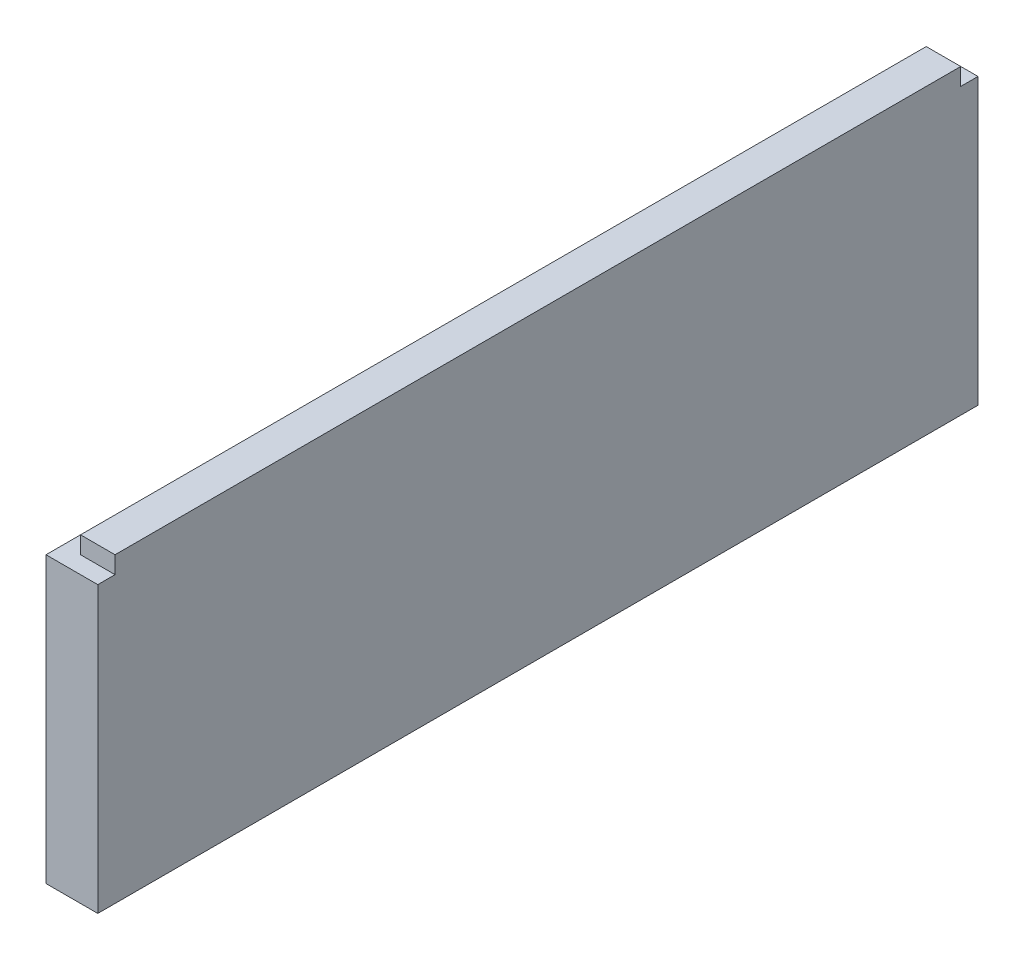
SolidWorks part; units mm, degrees
material "Сосна"
ref_plane "Спереди" through (0, 0, 0) normal (0, 0, 1) x (1, 0, 0)
ref_plane "Сверху" through (0, 0, 0) normal (0, 1, 0) x (1, 0, 0)
ref_plane "Справа" through (0, 0, 0) normal (1, 0, 0) x (0, 0, -1)
sketch "Эскиз1" plane through (0, 0, 0) normal (0, 0, 1) x (1, 0, 0)
  line L0 (0, 0) -> (10, 0)
  line L2 (10, 0) -> (30, 0)
  line L3 (30, 0) -> (30, 175)
  line L5 (10, 175) -> (10, 165)
  line L6 (10, 165) -> (0, 165)
  line L7 (0, 165) -> (0, 0)
  line L8 (30, 175) -> (10, 175)
  dimension "D1" = 175
  dimension "D2" = 30
  dimension "D3" = 10
  dimension "D5" = 10
extrude "Бобышка-Вытянуть1" add sketch "Эскиз1" along normal blind 510
sketch "Эскиз2" plane through (30, 0, 0) normal (1, 0, 0) x (0, 0, -1)
  line L0 (-10, 175) -> (0, 175)
  line L1 (-510, 175) -> (-500, 175)
  line L2 (-510, 175) -> (-510, 165)
  line L3 (-510, 165) -> (-500, 165)
  line L4 (-500, 175) -> (-500, 165)
  line L5 (-10, 175) -> (-10, 165)
  line L6 (-10, 165) -> (0, 165)
  line L7 (0, 175) -> (0, 165)
  dimension "D1" = 10
  dimension "D2" = 10
  dimension "D3" = 2
extrude "Вырез-Вытянуть1" cut sketch "Эскиз2" against normal through all
